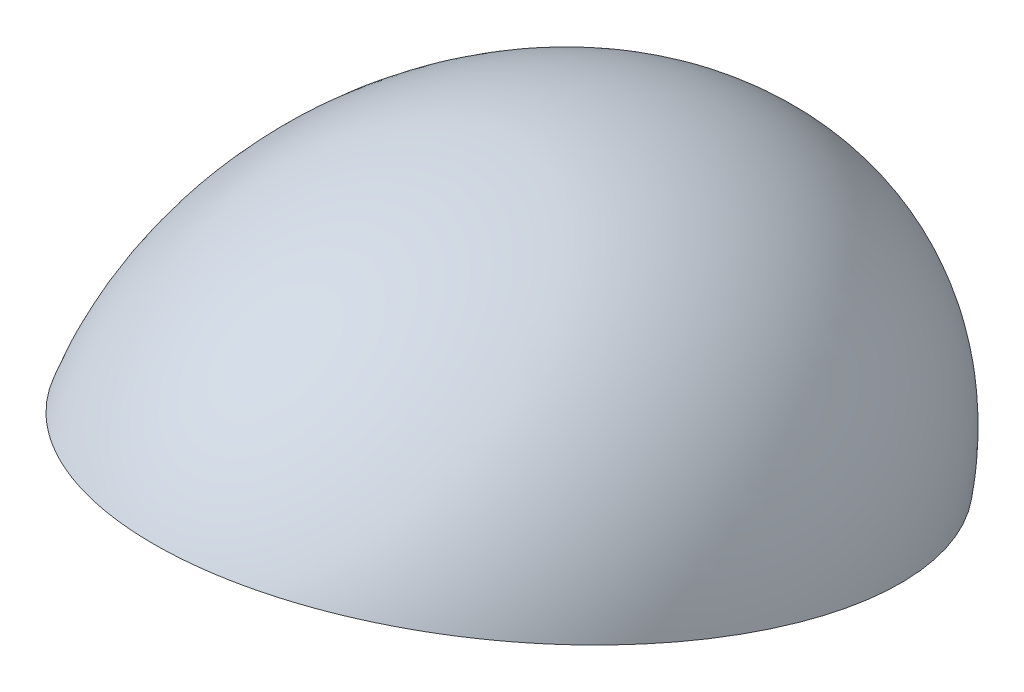
SolidWorks part; units mm, degrees
ref_plane "Front Plane" through (0, 0, 0) normal (0, 0, 1) x (1, 0, 0)
ref_plane "Top Plane" through (0, 0, 0) normal (0, 1, 0) x (1, 0, 0)
ref_plane "Right Plane" through (0, 0, 0) normal (1, 0, 0) x (0, 0, -1)
sketch "Sketch1" plane through (0, 0, 0) normal (0, 1, 0) x (1, 0, 0)
  line L0 (0, 0) -> (0, 50000) construction
  line L1 (0, 240) -> (0, -240)
  ellipse E0 centre (0, 0) end of major axis (0, -240) minor radius 190 (0, 240) -> (0, -240) ccw
revolve "Revolve1" add sketch "Sketch1" angle 360 about L1
sketch "Sketch2" plane through (0, 0, 0) normal (0, 1, 0) x (1, 0, 0)
  line L0 (0, 0) -> (375.6446, 0) construction
ref_plane "Plane1" through (0, 0, 0) normal (0, 0.9659, -0.2588) x (1, 0, 0)
ref_plane "Plane2" through (0, 19.3185, -5.1764) normal (0, 0.9659, -0.2588) x (1, 0, 0)
sketch "Sketch4" plane through (0, 19.3185, -5.1764) normal (0, 0.9659, -0.2588) x (1, 0, 0)
  line L1 (-272.9239, -342.9154) -> (272.9239, -342.9154)
  line L2 (-272.9239, -342.9154) -> (-272.9239, 342.9154)
  line L3 (-272.9239, 342.9154) -> (272.9239, 342.9154)
  line L4 (272.9239, -342.9154) -> (272.9239, 342.9154)
  line L5 (-272.9239, -342.9154) -> (272.9239, 342.9154) construction
  line L6 (-272.9239, 342.9154) -> (272.9239, -342.9154) construction
  point P0 (0, 0)
extrude "Cut-Extrude2" cut sketch "Sketch4" against normal through all
